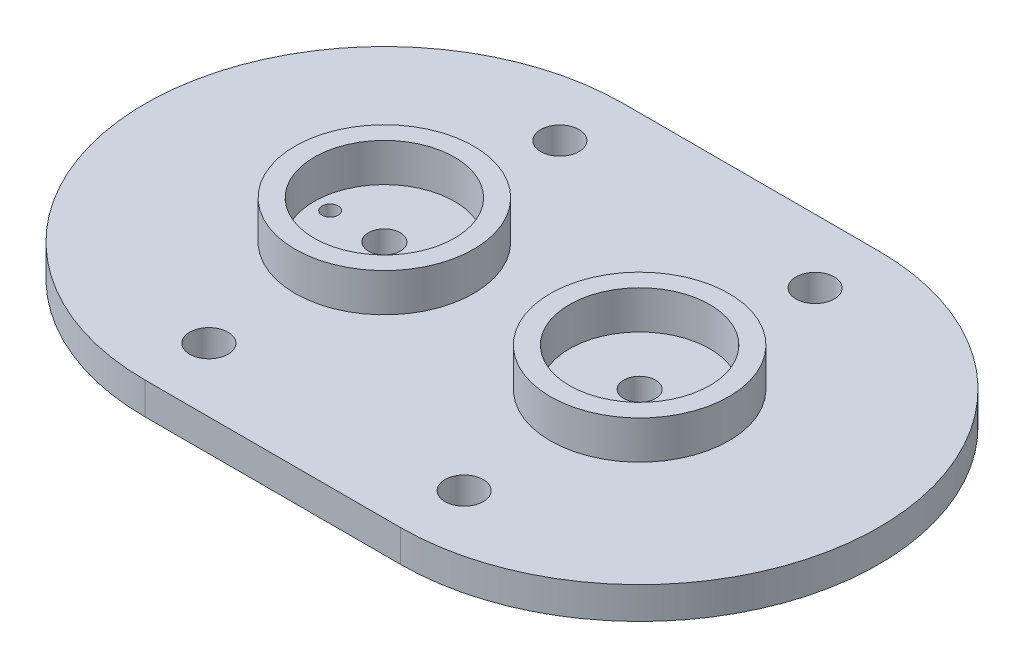
SolidWorks part; units mm, degrees
material "ABS"
ref_plane "Front" through (0, 0, 0) normal (0, 0, 1) x (1, 0, 0)
ref_plane "Top" through (0, 0, 0) normal (0, 1, 0) x (1, 0, 0)
ref_plane "Right" through (0, 0, 0) normal (1, 0, 0) x (0, 0, -1)
sketch "Croquis1" plane through (0, 0, 0) normal (0, 1, 0) x (1, 0, 0)
  line L0 (-20, 0) -> (20, 0) construction
  line L1 (-6.6, 0) -> (6.6, 0) construction
  line L2 (-20, 37.5) -> (20, 37.5)
  line L3 (-20, -37.5) -> (20, -37.5)
  line L4 (0, -6.6) -> (0, 6.6) construction
  arc A0 (-20, 37.5) -> (-20, -37.5) centre (-20, 0) ccw
  arc A1 (20, -37.5) -> (20, 37.5) centre (20, 0) ccw
  point P5 (0, 0)
  dimension "D2" = 37.5
  dimension "D1" = 40
extrude "Saliente-Extruir1" add sketch "Croquis1" along normal mid plane 5
sketch "Croquis2" plane through (0, 2.5, 0) normal (0, 1, 0) x (1, 0, 0)
  circle A0 centre (20, 0) radius 11
  circle A1 centre (-20, 0) radius 11
  circle A2 centre (-20, 0) radius 14
  circle A3 centre (20, 0) radius 14
  dimension "D1" = 22
  dimension "D2" = 3
extrude "Saliente-Extruir2" add sketch "Croquis2" along normal blind 6
sketch "Croquis8" plane through (0, -2.5, 0) normal (0, -1, 0) x (1, 0, 0)
  circle A0 centre (-20, 0) radius 15
  circle A1 centre (-20, 0) radius 3.75
  dimension "D1" = 7.5
  dimension "D2" = 30
extrude "Saliente-Extruir4" add sketch "Croquis8" along normal blind 2.5
fillet "Redondeo2" radius 1 2 edges at (-20, -2.5, -15) (-20, -5, -15)
sketch "Croquis6" plane through (0, 2.5, 0) normal (0, 1, 0) x (1, 0, 0)
  line L0 (-28.5, 0) -> (-11.5, 0) construction
  line L1 (-6.6, 0) -> (6.6, 0) construction
  line L3 (-20, -27.5) -> (20, -27.5) construction
  line L4 (-20, -27.5) -> (-20, 27.5) construction
  line L5 (-20, 27.5) -> (20, 27.5) construction
  line L6 (20, -27.5) -> (20, 27.5) construction
  line L7 (-20, -27.5) -> (20, 27.5) construction
  line L8 (-20, 27.5) -> (20, -27.5) construction
  circle A0 centre (-28.5, 0) radius 1.265
  circle A1 centre (-11.5, 0) radius 1.265
  circle A2 centre (-20, 0) radius 11 construction
  circle A3 centre (-20, 0) radius 2.5
  circle A4 centre (20, 0) radius 2.5
  circle A5 centre (-20, 27.5) radius 3
  circle A6 centre (20, 27.5) radius 3
  circle A7 centre (20, -27.5) radius 3
  circle A8 centre (-20, -27.5) radius 3
  point P7 (-20, 0)
  point P15 (0, 0)
  dimension "D1" = 2.53
  dimension "D3" = 5
  dimension "D6" = 6
  dimension "D2" = 17
  dimension "D4" = 40
  dimension "D5" = 55
extrude "Cortar-Extruir1" cut sketch "Croquis6" against normal up to next
